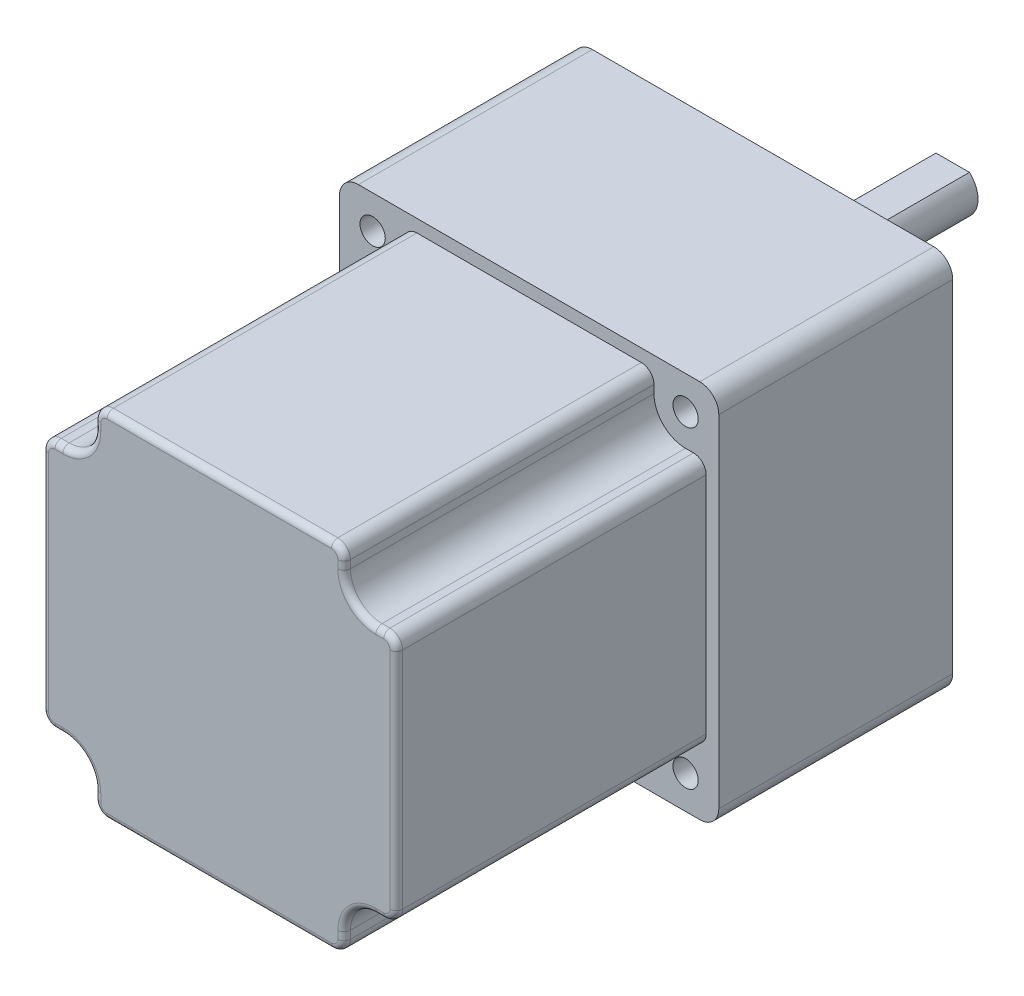
SolidWorks part; units mm, degrees
ref_plane "Спереди" through (0, 0, 0) normal (0, 0, 1) x (1, 0, 0)
ref_plane "Сверху" through (0, 0, 0) normal (0, 1, 0) x (1, 0, 0)
ref_plane "Справа" through (0, 0, 0) normal (1, 0, 0) x (0, 0, -1)
sketch "Эскиз1" plane through (0, 0, 0) normal (0, 0, 1) x (1, 0, 0)
  line L1 (-29.428, 23.0724) -> (30.572, 23.0724)
  line L2 (-29.428, 23.0724) -> (-29.428, -36.9276)
  line L3 (-29.428, -36.9276) -> (30.572, -36.9276)
  line L4 (30.572, 23.0724) -> (30.572, -36.9276)
  dimension "D1" = 60
  dimension "D2" = 60
extrude "Бобышка-Вытянуть1" add sketch "Эскиз1" along normal blind 37
sketch "Эскиз2" plane through (0, 0, 37) normal (0, 0, 1) x (1, 0, 0)
  line L0 (0.572, 23.0724) -> (0.572, -36.9276) construction
  line L1 (-27.428, 21.0724) -> (28.572, 21.0724)
  line L2 (-27.428, 21.0724) -> (-27.428, -34.9276)
  line L3 (-27.428, -34.9276) -> (28.572, -34.9276)
  line L4 (28.572, 21.0724) -> (28.572, -34.9276)
  line L5 (30.572, 23.0724) -> (-29.428, 23.0724) construction
  line L6 (-29.428, -36.9276) -> (30.572, -36.9276) construction
  line L7 (0.572, -36.9276) -> (30.572, -6.9276) construction
  line L8 (30.572, -36.9276) -> (30.572, 23.0724) construction
  line L9 (30.572, -6.9276) -> (-29.428, -6.9276) construction
  line L10 (-29.428, 23.0724) -> (-29.428, -36.9276) construction
  dimension "D1" = 56
  dimension "D2" = 56
  dimension "D3" = 28
  dimension "D4" = 28
extrude "Бобышка-Вытянуть2" add sketch "Эскиз2" along normal blind 49
sketch "Эскиз3" plane through (0, 0, 86) normal (0, 0, 1) x (1, 0, 0)
  line L0 (0.572, 21.0724) -> (0.572, -34.9276) construction
  line L1 (28.572, 21.0724) -> (-27.428, 21.0724) construction
  line L2 (-27.428, -34.9276) -> (28.572, -34.9276) construction
  line L3 (0.572, -34.9276) -> (28.572, -6.9276) construction
  line L4 (28.572, -34.9276) -> (28.572, 21.0724) construction
  line L5 (28.572, -6.9276) -> (-27.428, -6.9276) construction
  line L6 (-27.428, 21.0724) -> (-27.428, -34.9276) construction
  line L7 (0.572, -6.9276) -> (28.572, 21.0724) construction
  line L8 (-27.428, 21.0724) -> (0.572, -6.9276) construction
  line L9 (0.572, -6.9276) -> (-27.428, -34.9276) construction
  line L10 (0.572, -6.9276) -> (28.572, -34.9276) construction
  line L11 (-19.1767, 17.8211) -> (-19.1767, 21.0724)
  line L12 (28.572, 21.0724) -> (-27.428, 21.0724) construction
  line L13 (-24.1767, 12.8211) -> (-27.428, 12.8211)
  line L14 (-27.428, 12.8211) -> (-27.428, 21.0724)
  line L15 (-27.428, 21.0724) -> (-19.1767, 21.0724)
  line L16 (20.3208, 17.8211) -> (20.3208, 21.0724)
  line L17 (25.3208, 12.8211) -> (28.572, 12.8211)
  line L20 (20.3208, 21.0724) -> (28.572, 21.0724)
  line L21 (28.572, 21.0724) -> (28.572, 12.8211)
  line L22 (28.572, -34.9276) -> (28.572, 21.0724) construction
  line L23 (-24.1767, -26.6764) -> (-27.428, -26.6764)
  line L24 (-19.1767, -31.6764) -> (-19.1767, -34.9276)
  line L27 (-27.428, -26.6764) -> (-27.428, -34.9276)
  line L28 (-27.428, -34.9276) -> (-19.1767, -34.9276)
  line L29 (25.3208, -26.6764) -> (28.572, -26.6764)
  line L30 (20.3208, -31.6764) -> (20.3208, -34.9276)
  line L31 (20.3208, -34.9276) -> (28.572, -34.9276)
  line L32 (28.572, -34.9276) -> (28.572, -26.6764)
  circle A0 centre (0.572, -6.9276) radius 35 construction
  arc A1 (-24.1767, 12.8211) -> (-19.1767, 17.8211) centre (-24.1767, 17.8211) ccw
  arc A2 (20.3208, 17.8211) -> (25.3208, 12.8211) centre (25.3208, 17.8211) ccw
  arc A3 (-19.1767, -31.6764) -> (-24.1767, -26.6764) centre (-24.1767, -31.6764) ccw
  arc A4 (25.3208, -26.6764) -> (20.3208, -31.6764) centre (25.3208, -31.6764) ccw
  dimension "D1" = 70
  dimension "D2" = 10
  dimension "D3" = 10
  dimension "D4" = 10
  dimension "D5" = 10
extrude "Вырез-Вытянуть1" cut sketch "Эскиз3" against normal blind 49
sketch "Эскиз4" plane through (0, 0, 37) normal (0, 0, 1) x (1, 0, 0)
  circle A0 centre (-24.1767, 17.8211) radius 2
  circle A1 centre (25.3208, 17.8211) radius 2
  circle A2 centre (-24.1767, -31.6764) radius 2
  circle A3 centre (25.3208, -31.6764) radius 2
  dimension "D1" = 4
  dimension "D2" = 4
  dimension "D3" = 4
  dimension "D4" = 4
extrude "Вырез-Вытянуть2" cut sketch "Эскиз4" against normal blind 49
fillet "Скругление1" radius 2 8 edges at (28.572, 12.8211, 61.5) (20.3208, 21.0724, 61.5) (28.572, -26.6764, 61.5) (20.3208, -34.9276, 61.5) (-19.1767, -34.9276, 61.5) (-27.428, -26.6764, 61.5) (-19.1767, 21.0724, 61.5) (-27.428, 12.8211, 61.5)
sketch "Эскиз5" plane through (0, 0, 0) normal (0, 0, -1) x (-1, 0, 0)
  line L0 (-30.572, -6.9276) -> (29.428, -6.9276) construction
  line L1 (-30.572, -36.9276) -> (-30.572, 23.0724) construction
  line L2 (29.428, 23.0724) -> (29.428, -36.9276) construction
  line L3 (29.428, -6.9276) -> (-0.572, 23.0724) construction
  line L4 (-30.572, 23.0724) -> (29.428, 23.0724) construction
  line L5 (-0.572, 23.0724) -> (-0.572, -36.9276) construction
  line L6 (29.428, -36.9276) -> (-30.572, -36.9276) construction
  circle A0 centre (-0.572, -6.9276) radius 27
  dimension "D1" = 54
extrude "Вырез-Вытянуть3" cut sketch "Эскиз5" against normal blind 1
sketch "Эскиз6" plane through (0, 0, 1) normal (0, 0, -1) x (-1, 0, 0)
  line L0 (-0.572, 20.0724) -> (-0.572, -36.9276) construction
  line L1 (29.428, -36.9276) -> (-30.572, -36.9276) construction
  line L2 (-0.572, -36.9276) -> (29.428, -6.9276) construction
  line L3 (29.428, 23.0724) -> (29.428, -36.9276) construction
  line L4 (29.428, -6.9276) -> (-30.572, -6.9276) construction
  line L5 (-30.572, -36.9276) -> (-30.572, 23.0724) construction
  circle A0 centre (-0.572, -6.9276) radius 27 construction
  circle A1 centre (-0.572, -6.9276) radius 27 construction
  circle A2 centre (-0.572, 3.0724) radius 12
  dimension "D1" = 24
  dimension "D2" = 10
extrude "Бобышка-Вытянуть3" add sketch "Эскиз6" along normal blind 4
sketch "Эскиз7" plane through (0, 0, -3) normal (0, 0, -1) x (-1, 0, 0)
  circle A0 centre (-0.572, 3.0724) radius 4
  dimension "D1" = 8
extrude "Бобышка-Вытянуть4" add sketch "Эскиз7" along normal blind 27
sketch "Эскиз8" plane through (0, 0, -30) normal (0, 0, -1) x (-1, 0, 0)
  line L1 (-3.2178, 6.0724) -> (2.0737, 6.0724)
  line L2 (-3.2178, 6.0724) -> (-3.2178, 10.0287)
  line L3 (-3.2178, 10.0287) -> (2.0737, 10.0287)
  line L4 (2.0737, 6.0724) -> (2.0737, 10.0287)
  circle A0 centre (-0.572, 3.0724) radius 4 construction
  circle A1 centre (-0.572, 3.0724) radius 4 construction
  dimension "D1" = 3
extrude "Вырез-Вытянуть4" cut sketch "Эскиз8" against normal blind 27
fillet "Скругление2" radius 1 24 edges at (-24.8023, -26.6764, 86) (-26.8422, -26.0906, 86) (-20.6412, -28.1408, 86) (-19.1767, -32.302, 86) (-18.5909, -34.3418, 86) (0.572, -34.9276, 86) (27.9862, -26.0906, 86) (25.9464, -26.6764, 86) (21.7852, -28.1408, 86) (20.3208, -32.302, 86) (19.735, -34.3418, 86) (28.572, -6.9276, 86) (27.9862, 12.2353, 86) (25.9464, 12.8211, 86) (21.7852, 14.2856, 86) (20.3208, 18.4467, 86) (19.735, 20.4866, 86) (0.572, 21.0724, 86) (-18.5909, 20.4866, 86) (-19.1767, 18.4467, 86) (-20.6412, 14.2856, 86) (-24.8023, 12.8211, 86) (-26.8422, 12.2353, 86) (-27.428, -6.9276, 86)
fillet "Скругление3" radius 3 4 edges at (-29.428, -36.9276, 18.5) (30.572, -36.9276, 18.5) (30.572, 23.0724, 18.5) (-29.428, 23.0724, 18.5)
